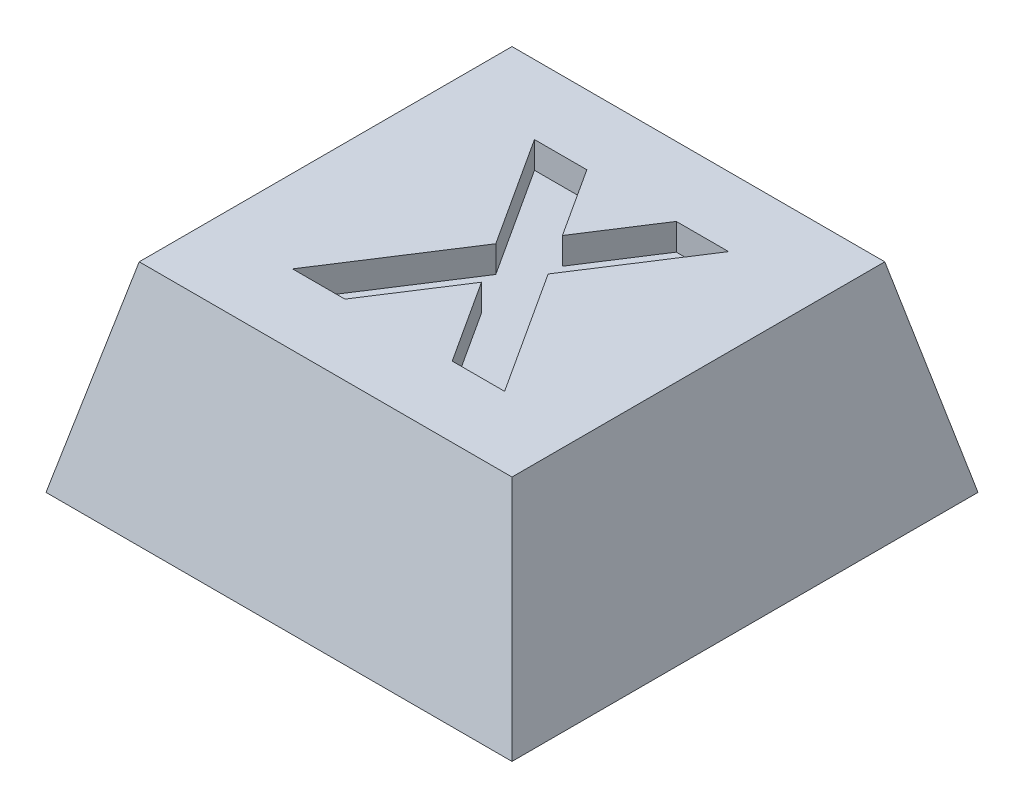
SolidWorks part; units mm, degrees
ref_plane "Front Plane" through (0, 0, 0) normal (0, 0, 1) x (1, 0, 0)
ref_plane "Top Plane" through (0, 0, 0) normal (0, 1, 0) x (1, 0, 0)
ref_plane "Right Plane" through (0, 0, 0) normal (1, 0, 0) x (0, 0, -1)
sketch "Sketch1" plane through (0, 0, 0) normal (0, 1, 0) x (1, 0, 0)
  line L1 (0, 0) -> (7, 0)
  line L2 (0, 0) -> (0, 7)
  line L3 (0, 7) -> (7, 7)
  line L4 (7, 0) -> (7, 7)
  dimension "D1" = 7
  dimension "D2" = 7
extrude "Boss-Extrude1" add sketch "Sketch1" along normal blind 3
sketch "Sketch2" plane through (0, 0, 0) normal (0, 0, 1) x (1, 0, 0)
  line L0 (0, 0) -> (0.7, 3)
  line L1 (0, 3) -> (7, 3) construction
  line L2 (0.7, 3) -> (0, 3)
  line L3 (0, 3) -> (0, 0)
  line L4 (7, 0) -> (6.3, 3)
  line L5 (6.3, 3) -> (7, 3)
  line L6 (7, 3) -> (7, 0)
  dimension "D1" = 0.7
  dimension "D2" = 0.7
extrude "Cut-Extrude1" cut sketch "Sketch2" against normal blind 7
sketch "Sketch3" plane through (0, 0, 0) normal (1, 0, 0) x (0, 0, -1)
  line L0 (0, 0) -> (0.7, 3)
  line L1 (7, 3) -> (0, 3) construction
  line L2 (0.7, 3) -> (0, 3)
  line L3 (0, 3) -> (0, 0)
  line L4 (7, 3) -> (6.3, 3)
  line L5 (6.3, 3) -> (7, 0)
  line L6 (7, 3) -> (7, 0)
  dimension "D1" = 0.7
  dimension "D2" = 0.7
extrude "Cut-Extrude2" cut sketch "Sketch3" along normal blind 11
sketch "Sketch4" plane through (0, 0, 0) normal (0, -1, 0) x (1, 0, 0)
  line L0 (3.5, 0) -> (3.5, -7) construction
  line L1 (0, 0) -> (7, 0) construction
  line L2 (7, -7) -> (0, -7) construction
  line L3 (0, -3.5) -> (7, -3.5) construction
  line L4 (0, -7) -> (0, 0) construction
  line L5 (7, 0) -> (7, -7) construction
  circle A0 centre (3.5, -3.5) radius 1.8
  dimension "D1" = 3.6
extrude "Cut-Extrude3" cut sketch "Sketch4" against normal blind 0.8
sketch "Sketch5" plane through (0, 3, 0) normal (0, 1, 0) x (1, 0, 0)
  text T0 "X" font "Arial" height 3.5
extrude "Cut-Extrude4" cut sketch "Sketch5" against normal blind 0.4
